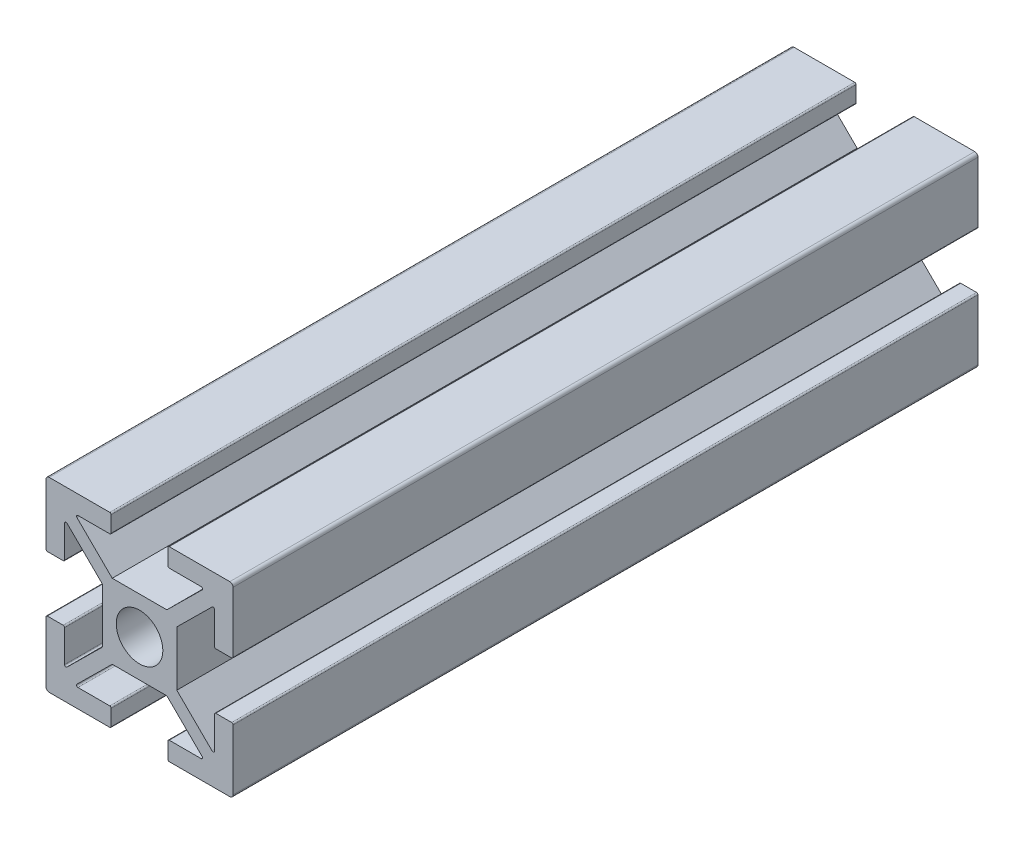
SolidWorks part; units mm, degrees
ref_plane "Front Plane" through (0, 0, 0) normal (0, 0, 1) x (1, 0, 0)
ref_plane "Top Plane" through (0, 0, 0) normal (0, 1, 0) x (1, 0, 0)
ref_plane "Right Plane" through (0, 0, 0) normal (1, 0, 0) x (0, 0, -1)
sketch "Sketch1" plane through (0, 0, 0) normal (0, 0, 1) x (1, 0, 0)
  line L0 (-7.4274, 2.1557) -> (-5.7274, 2.1557)
  line L1 (-0.7274, 9.1557) -> (-7.2274, 9.1557)
  line L2 (-7.5774, 2.3057) -> (-7.5774, 8.8057)
  line L3 (5.4021, 3.1557) -> (-0.4643, 3.1557)
  line L4 (-1.5311, -3.7897) -> (-1.5311, 2.1011)
  line L5 (-5.5774, 2.3057) -> (-5.5774, 5.7419)
  line L6 (-4.1455, 7.1557) -> (-0.7274, 7.1557)
  line L7 (-0.5774, 7.3057) -> (-0.5774, 9.0057)
  line L8 (-5.5774, 7.1557) -> (-1.5311, 3.1557) construction
  line L9 (-5.3219, 5.8486) -> (-1.5311, 2.1011)
  line L10 (-4.2509, 6.899) -> (-0.4643, 3.1557)
  line L11 (10.5152, 7.1557) -> (6.4689, 3.1557) construction
  line L12 (2.4689, -0.8443) -> (2.4689, 10.8443) construction
  line L13 (2.4689, -0.8443) -> (-12.5152, -0.8443) construction
  line L14 (9.1887, 6.899) -> (5.4021, 3.1557)
  line L15 (10.2598, 5.8486) -> (6.4689, 2.1011)
  line L16 (5.5152, 7.3057) -> (5.5152, 9.0057)
  line L17 (9.0833, 7.1557) -> (5.6652, 7.1557)
  line L18 (10.5152, 2.3057) -> (10.5152, 5.7419)
  line L19 (6.4689, -3.7897) -> (6.4689, 2.1011)
  line L20 (12.5152, 2.3057) -> (12.5152, 8.8057)
  line L21 (5.6652, 9.1557) -> (12.1652, 9.1557)
  line L22 (12.3652, 2.1557) -> (10.6652, 2.1557)
  line L23 (10.5152, -8.8443) -> (6.4689, -4.8443) construction
  line L24 (-5.5774, -8.8443) -> (-1.5311, -4.8443) construction
  line L25 (12.3652, -3.8443) -> (10.6652, -3.8443)
  line L26 (5.6652, -10.8443) -> (12.1652, -10.8443)
  line L27 (12.5152, -3.9943) -> (12.5152, -10.4943)
  line L28 (10.5152, -3.9943) -> (10.5152, -7.4305)
  line L29 (9.0833, -8.8443) -> (5.6652, -8.8443)
  line L30 (5.5152, -8.9943) -> (5.5152, -10.6943)
  line L31 (10.2598, -7.5372) -> (6.4689, -3.7897)
  line L32 (9.1887, -8.5876) -> (5.4021, -4.8443)
  line L33 (-4.2509, -8.5876) -> (-0.4643, -4.8443)
  line L34 (-5.3219, -7.5372) -> (-1.5311, -3.7897)
  line L35 (-0.5774, -8.9943) -> (-0.5774, -10.6943)
  line L36 (-4.1455, -8.8443) -> (-0.7274, -8.8443)
  line L37 (-5.5774, -3.9943) -> (-5.5774, -7.4305)
  line L38 (5.4021, -4.8443) -> (-0.4643, -4.8443)
  line L39 (-7.5774, -3.9943) -> (-7.5774, -10.4943)
  line L40 (-0.7274, -10.8443) -> (-7.2274, -10.8443)
  line L41 (-7.4274, -3.8443) -> (-5.7274, -3.8443)
  circle A0 centre (2.4689, -0.8443) radius 2.5
  arc A1 (-7.5774, 8.8057) -> (-7.2274, 9.1557) centre (-7.2274, 8.8057) cw
  arc A2 (-7.4274, 2.1557) -> (-7.5774, 2.3057) centre (-7.4274, 2.3057) cw
  arc A3 (-5.7274, 2.1557) -> (-5.5774, 2.3057) centre (-5.7274, 2.3057) ccw
  arc A4 (-0.7274, 9.1557) -> (-0.5774, 9.0057) centre (-0.7274, 9.0057) cw
  arc A5 (-0.7274, 7.1557) -> (-0.5774, 7.3057) centre (-0.7274, 7.3057) ccw
  arc A6 (-4.2509, 6.899) -> (-4.1455, 7.1557) centre (-4.1455, 7.0057) cw
  arc A7 (-5.3219, 5.8486) -> (-5.5774, 5.7419) centre (-5.4274, 5.7419) ccw
  arc A8 (10.2598, 5.8486) -> (10.5152, 5.7419) centre (10.3652, 5.7419) cw
  arc A9 (9.1887, 6.899) -> (9.0833, 7.1557) centre (9.0833, 7.0057) ccw
  arc A10 (5.6652, 7.1557) -> (5.5152, 7.3057) centre (5.6652, 7.3057) cw
  arc A11 (5.6652, 9.1557) -> (5.5152, 9.0057) centre (5.6652, 9.0057) ccw
  arc A12 (10.6652, 2.1557) -> (10.5152, 2.3057) centre (10.6652, 2.3057) cw
  arc A13 (12.3652, 2.1557) -> (12.5152, 2.3057) centre (12.3652, 2.3057) ccw
  arc A14 (12.5152, 8.8057) -> (12.1652, 9.1557) centre (12.1652, 8.8057) ccw
  arc A15 (12.5152, -10.4943) -> (12.1652, -10.8443) centre (12.1652, -10.4943) cw
  arc A16 (12.3652, -3.8443) -> (12.5152, -3.9943) centre (12.3652, -3.9943) cw
  arc A17 (10.6652, -3.8443) -> (10.5152, -3.9943) centre (10.6652, -3.9943) ccw
  arc A18 (5.6652, -10.8443) -> (5.5152, -10.6943) centre (5.6652, -10.6943) cw
  arc A19 (5.6652, -8.8443) -> (5.5152, -8.9943) centre (5.6652, -8.9943) ccw
  arc A20 (9.1887, -8.5876) -> (9.0833, -8.8443) centre (9.0833, -8.6943) cw
  arc A21 (10.2598, -7.5372) -> (10.5152, -7.4305) centre (10.3652, -7.4305) ccw
  arc A22 (-5.3219, -7.5372) -> (-5.5774, -7.4305) centre (-5.4274, -7.4305) cw
  arc A23 (-4.2509, -8.5876) -> (-4.1455, -8.8443) centre (-4.1455, -8.6943) ccw
  arc A24 (-0.7274, -8.8443) -> (-0.5774, -8.9943) centre (-0.7274, -8.9943) cw
  arc A25 (-0.7274, -10.8443) -> (-0.5774, -10.6943) centre (-0.7274, -10.6943) ccw
  arc A26 (-5.7274, -3.8443) -> (-5.5774, -3.9943) centre (-5.7274, -3.9943) cw
  arc A27 (-7.4274, -3.8443) -> (-7.5774, -3.9943) centre (-7.4274, -3.9943) ccw
  arc A28 (-7.5774, -10.4943) -> (-7.2274, -10.8443) centre (-7.2274, -10.4943) ccw
  point P27 (5.5152, 7.1557)
  point P28 (12.5152, -10.8443)
  point P47 (6.4689, -0.8443)
  point P57 (2.4689, 3.1557)
  point P59 (5.5152, 9.1557)
  point P60 (10.5152, 2.1557)
  point P61 (12.5152, 2.1557)
  point P62 (12.5152, 9.1557)
  point P112 (-1.5311, -0.8443)
  point P113 (12.5152, -3.8443)
  point P114 (10.5152, -3.8443)
  point P115 (5.5152, -10.8443)
  point P116 (2.4689, -4.8443)
  point P117 (-0.5774, -8.8443)
  point P118 (-0.5774, -10.8443)
  point P119 (-5.5774, -3.8443)
  point P120 (5.5152, -8.8443)
  point P121 (-7.5774, -3.8443)
  point P122 (-7.5774, -10.8443)
  dimension "D3" = 0.35
  dimension "D4" = 0.15
  dimension "D5" = 0.15
  dimension "D6" = 0.15
  dimension "D7" = 0.15
  dimension "D8" = 0.15
  dimension "D9" = 0.15
  dimension "D1" = 0.75
  dimension "D2" = 0.75
extrude "Boss-Extrude1" add sketch "Sketch1" along normal blind 80
